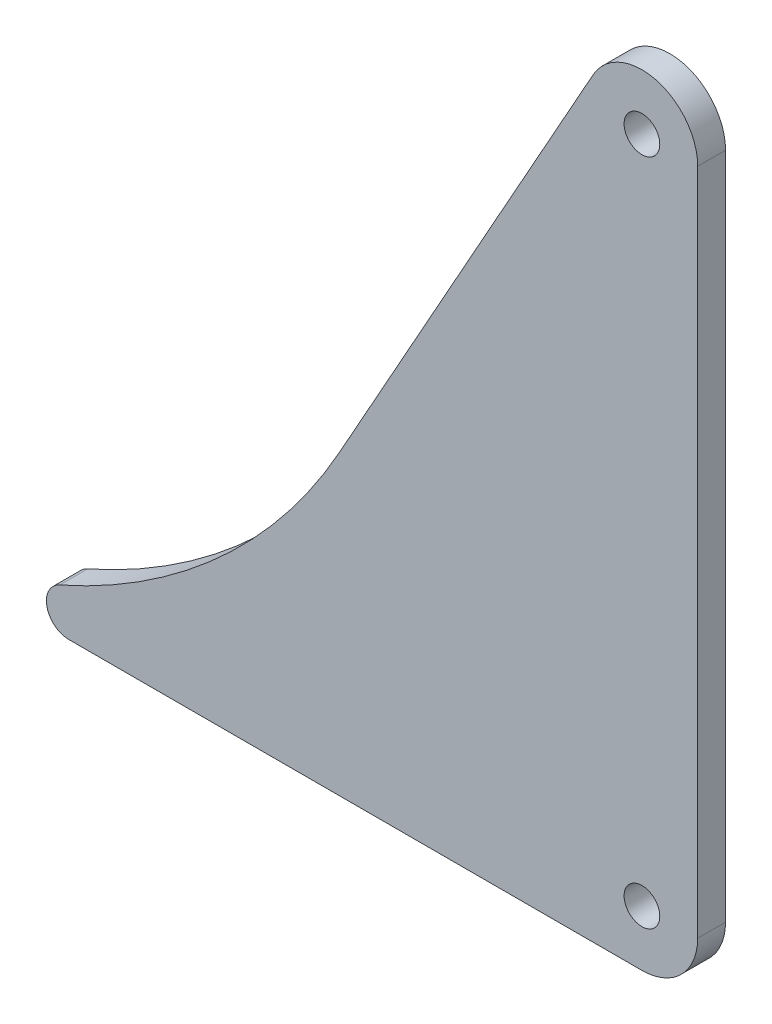
SolidWorks part; units mm, degrees
ref_plane "Front Plane" through (0, 0, 0) normal (0, 0, 1) x (1, 0, 0)
ref_plane "Top Plane" through (0, 0, 0) normal (0, 1, 0) x (1, 0, 0)
ref_plane "Right Plane" through (0, 0, 0) normal (1, 0, 0) x (0, 0, -1)
sketch "Sketch1" plane through (0, 0, 0) normal (0, 0, 1) x (1, 0, 0)
  line L0 (0, 0) -> (0, 106.8728)
  line L1 (0, 0) -> (-88.9, 0)
  line L2 (0, 106.8728) -> (-40.807, 33.8681)
  line L4 (135.3086, 348.943) -> (-17.145, 76.2) construction
  arc A0 (-88.9, 0) -> (-40.807, 33.8681) centre (-100.1307, 67.0279) ccw
  point P6 (-73.4075, 13.5013)
  point P7 (0, 68.7471)
  point P8 (0, 28.5929)
  point P9 (-35.0586, 45.8743)
  point P10 (0, 121.3367)
  point P11 (-32.3904, 57.5058)
  point P12 (0, 88.4643)
  point P15 (-19.2819, 50.7269)
  point P16 (-12.0696, 63.1143)
  point P17 (-39.5887, 40.924)
  point P18 (-44.5505, 32.402)
  point P19 (-141.6254, 123.2864)
  point P20 (-50.4521, 20.0208)
  point P21 (-47.9005, 24.5857)
  point P22 (-40.807, 33.8681)
  dimension "D2" = 88.9
extrude "Boss-Extrude1" add sketch "Sketch1" along normal blind 3.175
fillet "Fillet1" radius 2.54 1 edges at (-88.9, 0, 1.5875)
fillet "Fillet2" radius 6.35 2 edges at (0, 0, 1.5875) (0, 106.8728, 1.5875)
sketch "Sketch2" plane through (0, 0, 3.175) normal (0, 0, 1) x (1, 0, 0)
  circle A0 centre (-6.35, 6.35) radius 2.032
  circle A1 centre (-6.35, 82.4979) radius 2.032
  arc A2 (0, 82.4979) -> (-11.8929, 85.5962) centre (-6.35, 82.4979) ccw construction
  arc A3 (-6.35, 0) -> (0, 6.35) centre (-6.35, 6.35) ccw construction
  point P8 (0, 0)
  dimension "D3" = 4.064
extrude "Cut-Extrude1" cut sketch "Sketch2" against normal through all
